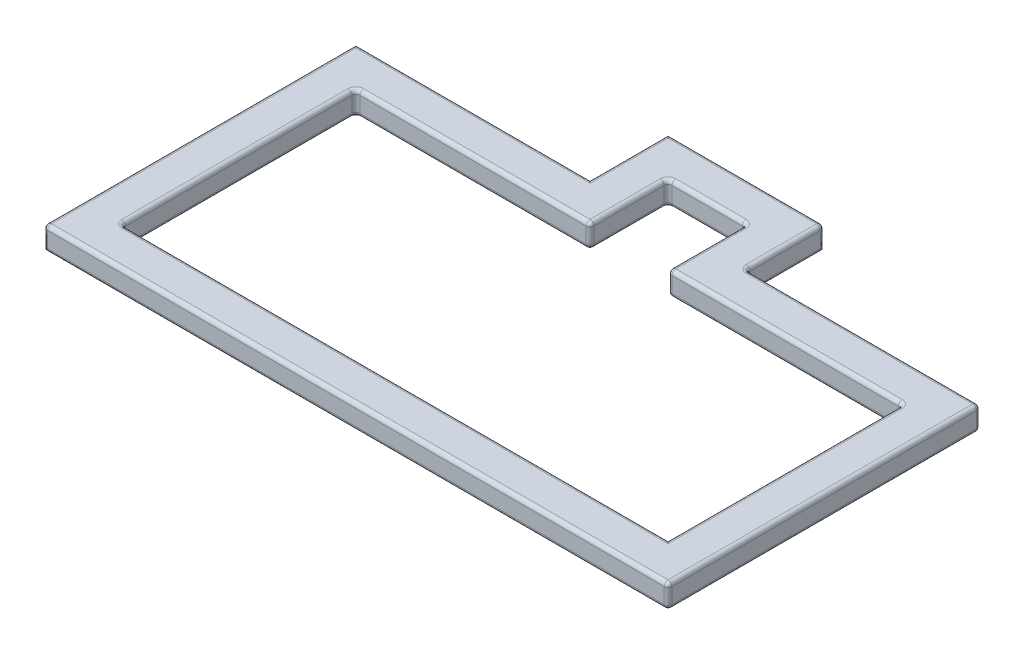
SolidWorks part; units mm, degrees
ref_plane "Front Plane" through (0, 0, 0) normal (0, 0, 1) x (1, 0, 0)
ref_plane "Top Plane" through (0, 0, 0) normal (0, 1, 0) x (1, 0, 0)
ref_plane "Right Plane" through (0, 0, 0) normal (1, 0, 0) x (0, 0, -1)
sketch "Sketch1" plane through (0, 0, 0) normal (0, 1, 0) x (1, 0, 0)
  line L1 (-399.8117, 283.9481) -> (-319.8117, 283.9481)
  line L2 (-399.8117, 283.9481) -> (-399.8117, 243.9481)
  line L3 (-399.8117, 243.9481) -> (-319.8117, 243.9481)
  line L4 (-319.8117, 283.9481) -> (-319.8117, 243.9481)
  line L5 (-394.8117, 278.9481) -> (-324.8117, 278.9481)
  line L6 (-394.8117, 278.9481) -> (-394.8117, 248.9481)
  line L7 (-394.8117, 248.9481) -> (-324.8117, 248.9481)
  line L8 (-324.8117, 278.9481) -> (-324.8117, 248.9481)
  line L17 (-364.8117, 288.9481) -> (-354.8117, 288.9481)
  line L18 (-369.8117, 293.9481) -> (-349.8117, 293.9481)
  line L19 (-369.8117, 293.9481) -> (-369.8117, 283.9481)
  line L20 (-369.8117, 283.9481) -> (-349.8117, 283.9481)
  line L21 (-349.8117, 293.9481) -> (-349.8117, 283.9481)
  line L22 (-364.8117, 288.9481) -> (-364.8117, 278.9481)
  line L23 (-364.8117, 278.9481) -> (-354.8117, 278.9481)
  line L24 (-354.8117, 288.9481) -> (-354.8117, 278.9481)
  dimension "D1" = 80
  dimension "D2" = 40
  dimension "D3" = 5
  dimension "D4" = 5
  dimension "D5" = 5
  dimension "D6" = 5
  dimension "D7" = 20
  dimension "D8" = 10
  dimension "D9" = 5
  dimension "D10" = 5
  dimension "D11" = 30
  dimension "D12" = 10
extrude "Boss-Extrude4" add sketch "Sketch1" along normal blind 3 contours L1 L24 L5 L8 L7 L6 L22 L2 L3 L4 | L17 L24 L1 L21 L18 L19 L22
fillet "Fillet1" radius 0.5 40 edges at (-334.8117, 3, -283.9481) (-334.8117, 0, -283.9481) (-354.8117, 0, -283.9481) (-354.8117, 3, -283.9481) (-324.8117, 0, -263.9481) (-324.8117, 3, -263.9481) (-359.8117, 0, -248.9481) (-359.8117, 3, -248.9481) (-349.8117, 0, -288.9481) (-349.8117, 3, -288.9481) (-359.8117, 0, -243.9481) (-359.8117, 3, -243.9481) (-319.8117, 0, -263.9481) (-319.8117, 3, -263.9481) (-359.8117, 0, -288.9481) (-359.8117, 3, -288.9481) (-339.8117, 0, -278.9481) (-339.8117, 3, -278.9481) (-394.8117, 0, -263.9481) (-394.8117, 3, -263.9481) (-379.8117, 0, -278.9481) (-379.8117, 3, -278.9481) (-364.8117, 0, -283.9481) (-364.8117, 3, -283.9481) (-359.8117, 3, -293.9481) (-369.8117, 3, -288.9481) (-384.8117, 3, -283.9481) (-399.8117, 3, -263.9481) (-319.8117, 1.5, -283.9481) (-319.8117, 1.5, -243.9481) (-399.8117, 1.5, -243.9481) (-349.8117, 1.5, -293.9481) (-349.8117, 1.5, -283.9481) (-364.8117, 1.5, -288.9481) (-364.8117, 1.5, -278.9481) (-394.8117, 1.5, -278.9481) (-394.8117, 1.5, -248.9481) (-324.8117, 1.5, -278.9481) (-354.8117, 1.5, -278.9481) (-354.8117, 1.5, -288.9481)
equation "\"ScannerWidth\" = 80"
equation "\"ScannerLength\" = 40"
equation "\"SpineLength\" = 10"
equation "\"ScannerThickness\" = 5"
equation "\"D1@Sketch1\"=\"ScannerWidth\""
equation "\"D2@Sketch1\"=\"ScannerLength\""
equation "\"D3@Sketch1\"=\"ScannerThickness\""
equation "\"D4@Sketch1\"=\"ScannerThickness\""
equation "\"D5@Sketch1\"=\"ScannerThickness\""
equation "\"ScannerHeight\" = 3"
equation "\"SpineWidth\"= 10"
equation "\"D7@Sketch1\"=\"ScannerThickness\"*2+\"SpineWidth\""
equation "\"D6@Sketch1\"= \"ScannerThickness\""
equation "\"D9@Sketch1\"=\"ScannerThickness\""
equation "\"D8@Sketch1\"=\"SpineWidth\""
equation "\"D10@Sketch1\"=\"ScannerThickness\""
equation "\"D11@Sketch1\"=(\"ScannerWidth\"-\"SpineWidth\"-\"ScannerThickness\"*2)/2"
equation "\"D1@Boss-Extrude4\"=\"ScannerHeight\""
equation "\"D12@Sketch1\"=\"SpineLength\""
